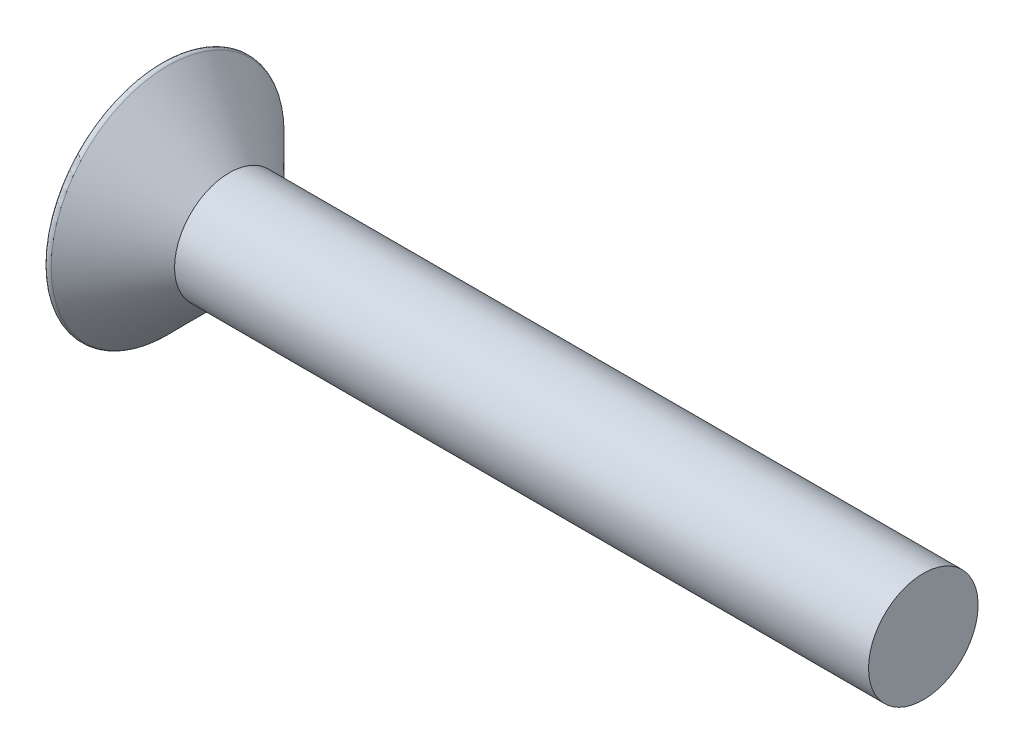
SolidWorks part; units mm, degrees
ref_plane "Plan de face" through (0, 0, 0) normal (0, 0, 1) x (1, 0, 0)
ref_plane "Plan de dessus" through (0, 0, 0) normal (0, 1, 0) x (1, 0, 0)
ref_plane "Plan de droite" through (0, 0, 0) normal (1, 0, 0) x (0, 0, -1)
sketch "Esquisse1" plane through (0, 0, 0) normal (0, 0, 1) x (1, 0, 0)
  line L0 (0, 0) -> (20.86, 0) construction
  line L1 (0, 0) -> (0, 3.36)
  line L2 (0, 3.36) -> (1.86, 1.5)
  line L3 (1.86, 1.5) -> (20.86, 1.5)
  line L4 (20.86, 1.5) -> (20.86, 0)
  line L5 (0, 0) -> (20.86, 0)
  dimension "D1" = 3.36
  dimension "D2" = 1.86
  dimension "D3" = 45
  dimension "D4" = 19
revolve "Révolution1" add sketch "Esquisse1" angle 360 about L0
fillet "Congé1" radius 0.1 1 edges at (0, 0, 3.36)
